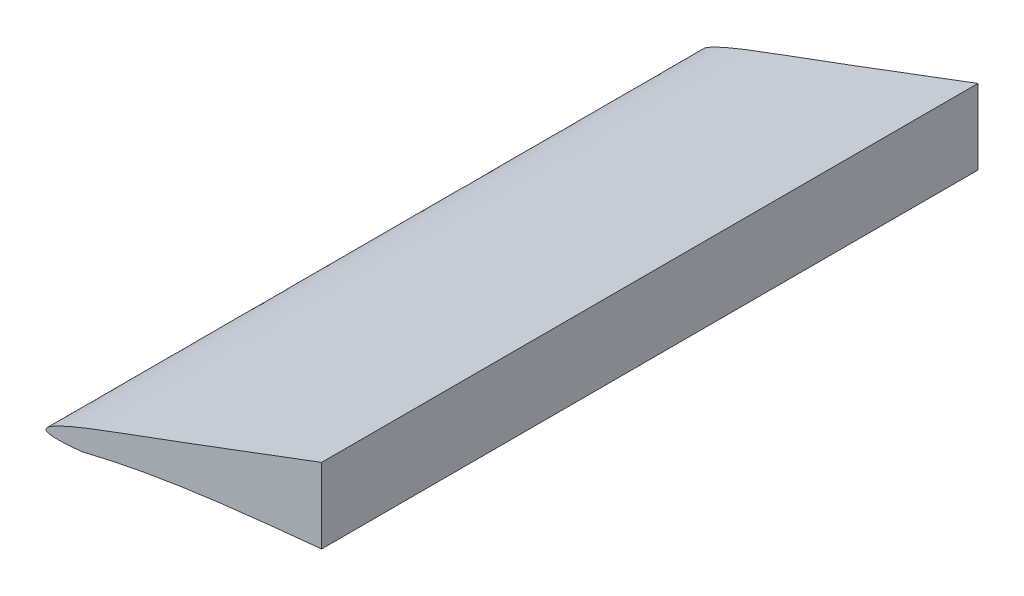
SolidWorks part; units mm, degrees
ref_plane "Front Plane" through (0, 0, 0) normal (0, 0, 1) x (1, 0, 0)
ref_plane "Top Plane" through (0, 0, 0) normal (0, 1, 0) x (1, 0, 0)
ref_plane "Right Plane" through (0, 0, 0) normal (1, 0, 0) x (0, 0, -1)
sketch "Sketch1" plane through (0, 0, 0) normal (0, 0, 1) x (1, 0, 0)
  circle A2 centre (19.9332, 5.0443) radius 2.032
  arc A3 (20.568, -2.2627) -> (27.5519, 5.1875) centre (19.9332, 5.3308) ccw
  arc A4 (27.5519, 5.1875) -> (17.8991, 12.3878) centre (19.9332, 5.0443) ccw
  spline S0 degree 3 poles (-43.5668, -9.1185) (-37.6773, -7.6477) (-27.7099, -7.0247) (-9.9845, -4.6043) (5.4332, -3.6912) (16.9241, -2.5678) (20.5343, -2.2656) (20.568, -2.2627) knots 0.794337 0.794337 0.794337 0.794337 0.852124 0.889612 0.965358 0.999676 1 1 1 1
  spline S1 degree 3 poles (17.8991, 12.3878) (11.779, 10.6925) (-2.9586, 6.4319) (-24.0803, -0.4076) (-34.9936, -4.7358) (-48.5374, -9.6348) (-43.5668, -9.1185) knots 0 0 0 0 0.056261 0.133579 0.179881 0.203823 0.203823 0.203823 0.203823
extrude "Boss-Extrude1" add sketch "Sketch1" along normal blind 39.37
sketch "Sketch3" plane through (0, 0, 39.37) normal (0, 0, 1) x (1, 0, 0)
  line L1 (-29.21, 22.9786) -> (35.7214, 22.9786)
  line L2 (-29.21, 22.9786) -> (-29.21, -18.2729)
  line L3 (-29.21, -18.2729) -> (35.7214, -18.2729)
  line L4 (35.7214, 22.9786) -> (35.7214, -18.2729)
  dimension "D1" = 29.21
extrude "Cut-Extrude2" cut sketch "Sketch3" against normal through all both
